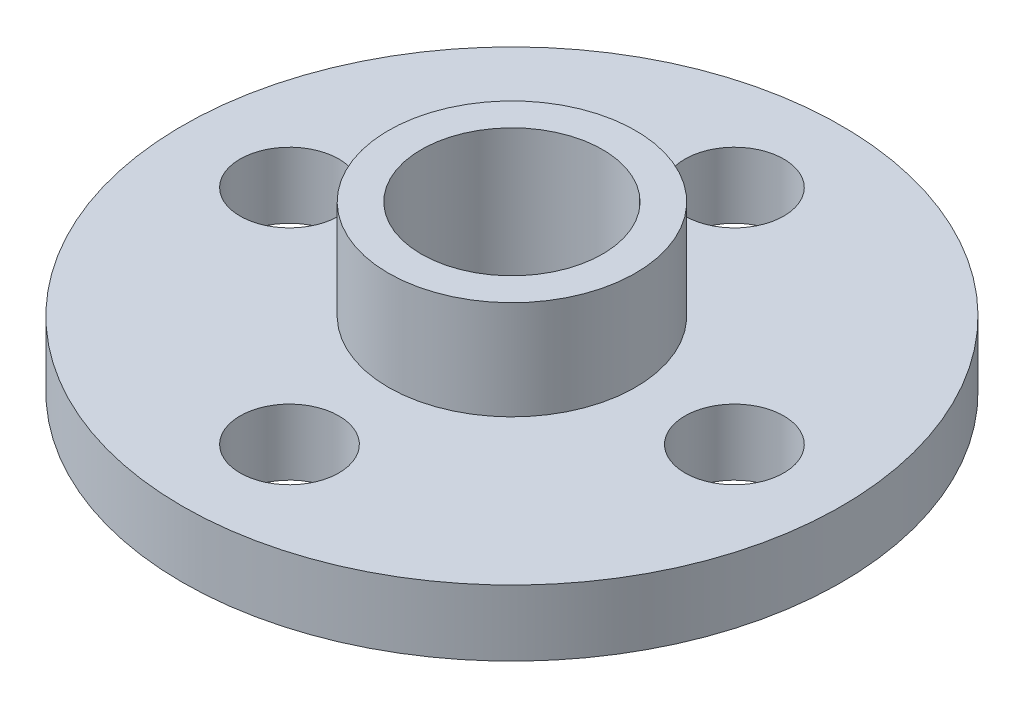
SolidWorks part; units mm, degrees
material "1060 Alloy"
ref_plane "Front Plane" through (0, 0, 0) normal (0, 0, 1) x (1, 0, 0)
ref_plane "Top Plane" through (0, 0, 0) normal (0, 1, 0) x (1, 0, 0)
ref_plane "Right Plane" through (0, 0, 0) normal (1, 0, 0) x (0, 0, -1)
sketch "Sketch2" plane through (0, 0, 0) normal (0, 1, 0) x (1, 0, 0)
  circle A0 centre (0, 0) radius 10
  dimension "D1" = 20
extrude "Boss-Extrude1" add sketch "Sketch2" along normal blind 2
sketch "Sketch3" plane through (0, 2, 0) normal (0, 1, 0) x (1, 0, 0)
  line L0 (0, 0) -> (0, 12.6294) construction
  line L1 (0, 0) -> (16.4383, 0) construction
  circle A1 centre (0, 6.75) radius 1.5
  circle A2 centre (6.75, 0) radius 1.5
  circle A3 centre (0, -6.75) radius 1.5
  circle A4 centre (-6.75, 0) radius 1.5
  dimension "D1" = 13.5
  dimension "D3" = 3
  dimension "D2" = 13.5
extrude "Cut-Extrude1" cut sketch "Sketch3" against normal through all
sketch "Sketch4" plane through (0, 2, 0) normal (0, 1, 0) x (1, 0, 0)
  circle A0 centre (0, 0) radius 3.75
  dimension "D1" = 7.5
extrude "Boss-Extrude2" add sketch "Sketch4" along normal blind 3
sketch "Sketch5" plane through (0, 5, 0) normal (0, 1, 0) x (1, 0, 0)
  circle A0 centre (0, 0) radius 1.5
  dimension "D1" = 3
extrude "Cut-Extrude2" cut sketch "Sketch5" against normal through all
sketch "Sketch6" plane through (0, 5, 0) normal (0, 1, 0) x (1, 0, 0)
  circle A0 centre (0, 0) radius 2.75
  dimension "D1" = 5.5
extrude "Cut-Extrude3" cut sketch "Sketch6" against normal blind 4.5
